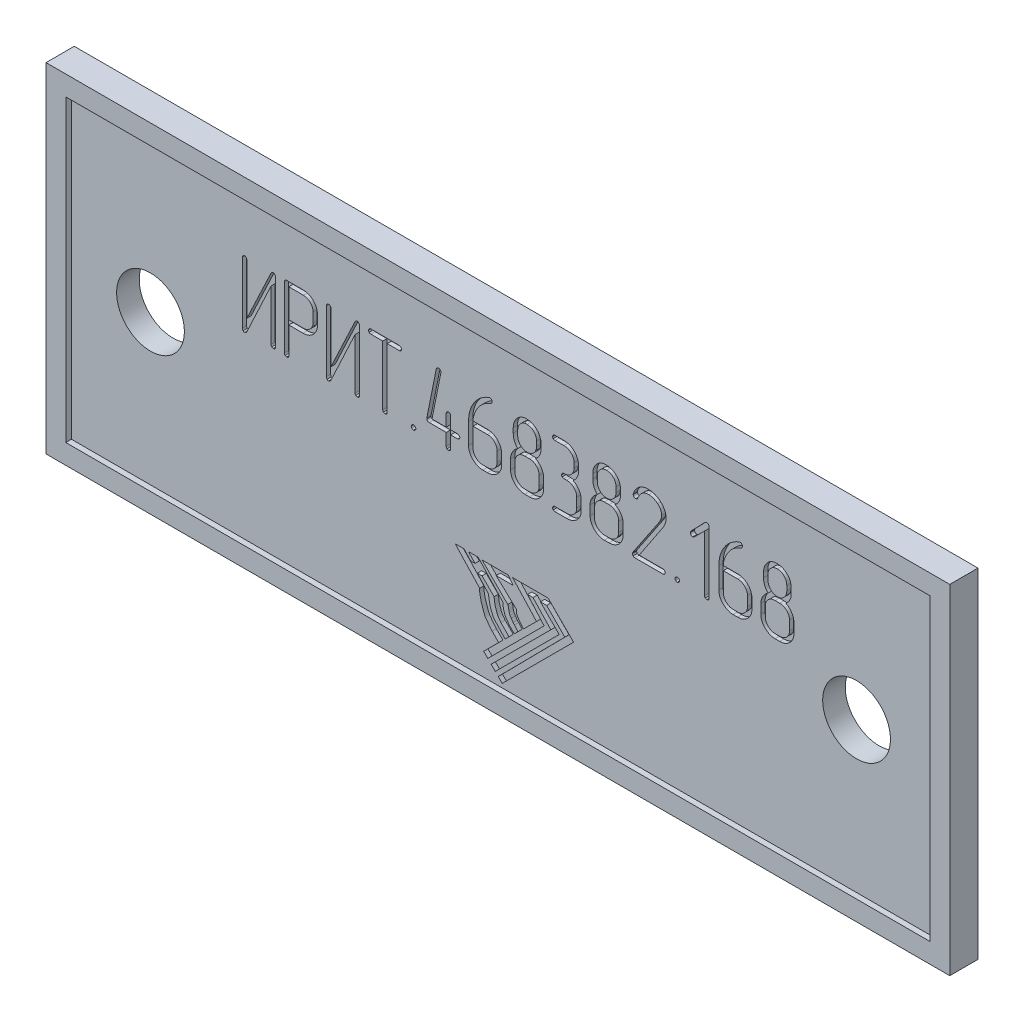
SolidWorks part; units mm, degrees
ref_plane "Спереди" through (0, 0, 0) normal (0, 0, 1) x (1, 0, 0)
ref_plane "Сверху" through (0, 0, 0) normal (0, 1, 0) x (1, 0, 0)
ref_plane "Справа" through (0, 0, 0) normal (1, 0, 0) x (0, 0, -1)
sketch "Эскиз1" plane through (0, 0, 0) normal (0, 0, 1) x (1, 0, 0)
  line L1 (-16, 6) -> (16, 6)
  line L2 (-16, 6) -> (-16, -6)
  line L3 (-16, -6) -> (16, -6)
  line L4 (16, 6) -> (16, -6)
  line L5 (0, -6) -> (0, 6) construction
  line L6 (-16, 0) -> (16, 0) construction
  point P0 (0, 0)
  dimension "D1" = 32
  dimension "D2" = 12
extrude "Бобышка-Вытянуть1" add sketch "Эскиз1" along normal mid plane 1
sketch "Эскиз2" plane through (0, 0, 0.5) normal (0, 0, 1) x (1, 0, 0)
  line L14 (15.3, -5.3) -> (15.3, 5.3)
  line L15 (-15.3, -5.3) -> (15.3, -5.3)
  line L16 (-15.3, 5.3) -> (-15.3, -5.3)
  line L17 (15.3, 5.3) -> (-15.3, 5.3)
  line L18 (15.3, -5.3) -> (15.3, 5.3)
  line L19 (-15.3, -5.3) -> (15.3, -5.3)
  line L20 (-15.3, 5.3) -> (-15.3, -5.3)
  line L21 (15.3, 5.3) -> (-15.3, 5.3)
  dimension "D1" = 0.7
extrude "Вырез-Вытянуть1" cut sketch "Эскиз2" against normal blind 0.2
sketch "Эскиз3" plane through (0, 0, 0.3) normal (0, 0, 1) x (1, 0, 0)
  line L0 (-16, -6) -> (16, -6) construction
  line L1 (0, 4.4961) -> (0, -4.0278) construction
  circle A0 centre (-12.5, 0) radius 1.2
  circle A1 centre (12.5, 0) radius 1.2
  dimension "D1" = 2.4
  dimension "D2" = 6
  dimension "D3" = 12.5
extrude "Вырез-Вытянуть2" cut sketch "Эскиз3" against normal blind 4.2
sketch "Эскиз4" plane through (0, 0, 0.3) normal (0, 0, 1) x (1, 0, 0)
  line L0 (0.1672, -3.296) -> (0.1672, 0.8064) construction
sketch "Эскиз5" plane through (0, 0, 0.3) normal (0, 0, 1) x (1, 0, 0)
  line L0 (-0.7033, -4.5023) -> (-0.5571, -4.6484)
  line L1 (-0.0459, -5.1596) -> (2.4804, -2.6333)
  line L2 (2.4804, -2.6333) -> (1.578, -1.7308)
  line L3 (1.578, -1.7308) -> (0.3213, -1.7308)
  line L5 (0.2903, -1.8939) -> (0.1666, -1.7308)
  line L6 (0.1666, -1.7308) -> (-0.761, -1.7308)
  line L8 (-0.761, -1.8661) -> (-0.9007, -1.7162)
  line L9 (-0.9007, -1.7162) -> (-1.2416, -1.7162)
  line L11 (-1.2416, -1.8807) -> (-1.401, -1.7097)
  line L12 (-1.401, -1.7097) -> (-1.7111, -1.7097)
  line L18 (-0.1872, -5.0183) -> (2.1701, -2.6333)
  line L19 (2.1701, -2.6333) -> (1.5278, -1.9819)
  line L20 (1.5278, -1.9819) -> (1.3065, -1.9819)
  line L21 (1.3065, -1.9819) -> (1.9692, -2.6539)
  line L22 (1.9692, -2.6539) -> (-0.2912, -4.9143)
  line L23 (-0.4379, -4.7677) -> (1.6758, -2.6539)
  line L24 (1.6758, -2.6539) -> (1.0424, -1.9819)
  line L25 (1.0424, -1.9819) -> (0.8518, -1.9819)
  line L26 (0.8518, -1.9819) -> (1.4374, -2.6539)
  line L27 (1.4374, -2.6539) -> (-0.5571, -4.6484)
  line L28 (0.3213, -1.7308) -> (1.1676, -2.6539)
  line L29 (1.1676, -2.6539) -> (0.7041, -3.1175)
  line L30 (0.7041, -3.1175) -> (0.5366, -2.8998)
  line L31 (0.4554, -2.6333) -> (0.4554, -2.7028)
  line L32 (0.4554, -2.6333) -> (-0.2621, -1.9609)
  line L33 (-0.2621, -1.9609) -> (0.3423, -1.9609)
  line L34 (0.3423, -1.9609) -> (0.2903, -1.8939)
  line L35 (-0.0212, -2.6539) -> (-0.761, -1.8661)
  line L36 (-0.761, -1.7308) -> (0.1488, -2.6406)
  line L37 (0.2307, -2.935) -> (0.2754, -3.0065)
  line L38 (0.2754, -3.0065) -> (0.3423, -3.106)
  line L39 (0.3423, -3.106) -> (0.3842, -3.151)
  line L40 (0.3842, -3.151) -> (0.5086, -3.2989)
  line L41 (0.5086, -3.2989) -> (0.3842, -3.4241)
  line L42 (-1.2416, -1.8807) -> (-1.1663, -1.9609)
  line L43 (-1.1663, -1.9609) -> (-1.0083, -1.9609)
  line L44 (-1.0083, -1.9609) -> (-1.2416, -1.7162)
  line L45 (-0.9251, -2.2176) -> (-0.761, -2.2176)
  line L46 (-0.761, -2.2176) -> (-0.3349, -2.6437)
  line L47 (-0.9251, -2.2176) -> (-0.5479, -2.6406)
  line L48 (-0.3612, -3.2931) -> (0.0556, -3.7469)
  line L49 (0.0556, -3.7469) -> (0.1947, -3.6094)
  line L50 (0.1947, -3.6094) -> (-0.0923, -3.3189)
  line L51 (-0.4031, -3.1862) -> (-0.3612, -3.2931)
  line L52 (-1.7111, -1.7097) -> (-0.843, -2.6406)
  line L53 (-0.7033, -4.5023) -> (-0.1706, -3.9696)
  line L54 (-0.1706, -3.9696) -> (-0.4031, -3.7371)
  line L55 (-0.1872, -5.0183) -> (-0.0459, -5.1596)
  line L56 (-0.4379, -4.7677) -> (-0.2912, -4.9143)
  spline S1 degree 3 poles (0.5366, -2.8998) (0.5134, -2.8614) (0.473, -2.8009) (0.454, -2.73) (0.4554, -2.7028) knots 0 0 0 0 0.624963 1 1 1 1
  spline S2 degree 3 poles (0.3842, -3.4241) (0.3311, -3.3772) (0.2568, -3.3112) (0.1772, -3.2116) (0.1278, -3.1381) (0.0638, -3.0525) (0.0064, -2.8873) (-0.0299, -2.7528) (-0.0212, -2.6539) knots 0 0 0 0 0.236603 0.329099 0.42399 0.531883 0.682853 1 1 1 1
  spline S3 degree 3 poles (0.1488, -2.6406) (0.1629, -2.67) (0.1807, -2.7248) (0.1854, -2.8037) (0.2036, -2.8713) (0.2139, -2.9164) (0.2307, -2.935) knots 0 0 0 0 0.317088 0.555738 0.765082 1 1 1 1
  spline S4 degree 3 poles (-0.5479, -2.6406) (-0.5345, -2.6519) (-0.5361, -2.6844) (-0.523, -2.7244) (-0.5207, -2.7728) (-0.5104, -2.8338) (-0.4951, -2.9007) (-0.484, -2.9657) (-0.4707, -3.0157) (-0.4488, -3.0913) (-0.4205, -3.1445) (-0.4031, -3.1862) knots 0 0 0 0 0.084251 0.160376 0.222667 0.338089 0.486926 0.584849 0.685663 0.760094 1 1 1 1
  spline S5 degree 3 poles (-0.0923, -3.3189) (-0.1277, -3.2771) (-0.1708, -3.2123) (-0.2238, -3.1289) (-0.2441, -3.057) (-0.27, -2.9868) (-0.2925, -2.9038) (-0.3163, -2.8276) (-0.314, -2.7413) (-0.3383, -2.6672) (-0.3349, -2.6437) knots 0 0 0 0 0.19218 0.276773 0.345923 0.454705 0.540608 0.651164 0.728926 0.859286 0.859286 0.859286 0.859286
  spline S6 degree 3 poles (-0.4031, -3.7371) (-0.4797, -3.6526) (-0.5619, -3.5342) (-0.6739, -3.3842) (-0.6978, -3.2807) (-0.7397, -3.1915) (-0.7581, -3.1023) (-0.7965, -3.0265) (-0.8077, -2.9393) (-0.8404, -2.8154) (-0.8506, -2.7122) (-0.843, -2.6406) knots 0 0 0 0 0.278751 0.363226 0.457923 0.537759 0.60667 0.682233 0.745611 0.822853 1 1 1 1
extrude "Вырез-Вытянуть3" cut sketch "Эскиз5" against normal blind 0.15
sketch "Эскиз6" plane through (0, 0, 0.3) normal (0, 0, 1) x (1, 0, 0)
  line L0 (-9.4044, 1.0401) -> (9.3368, 1.0401) construction
  text T0 "ИРИТ.468382.168" font "Mipgost" height in points 9
extrude "Вырез-Вытянуть4" cut sketch "Эскиз6" against normal blind 0.15
